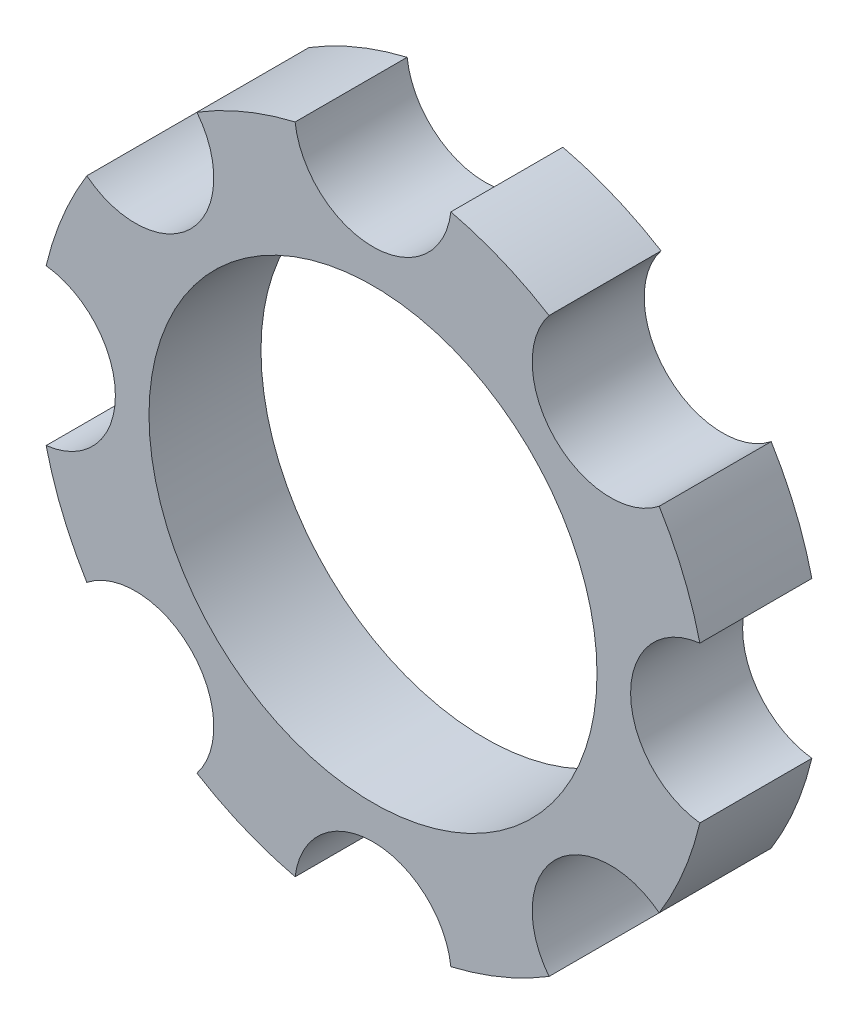
SolidWorks part; units mm, degrees
ref_plane "Front Plane" through (0, 0, 0) normal (0, 0, 1) x (1, 0, 0)
ref_plane "Top Plane" through (0, 0, 0) normal (0, 1, 0) x (1, 0, 0)
ref_plane "Right Plane" through (0, 0, 0) normal (1, 0, 0) x (0, 0, -1)
sketch "Sketch1" plane through (0, 0, 0) normal (0, 0, 1) x (1, 0, 0)
  circle A0 centre (0, 0) radius 20
  arc A1 (-6.9522, 29.1833) -> (-15.7198, 25.5517) centre (0, 0) ccw
  arc A2 (-6.9522, 29.1833) -> (6.9522, 29.1833) centre (0, 30) ccw
  arc A3 (15.7198, 25.5517) -> (25.5517, 15.7198) centre (21.2132, 21.2132) ccw
  arc A4 (29.1833, 6.9522) -> (29.1833, -6.9522) centre (30, 0) ccw
  arc A5 (25.5517, -15.7198) -> (15.7198, -25.5517) centre (21.2132, -21.2132) ccw
  arc A6 (6.9522, -29.1833) -> (-6.9522, -29.1833) centre (0, -30) ccw
  arc A7 (-15.7198, -25.5517) -> (-25.5517, -15.7198) centre (-21.2132, -21.2132) ccw
  arc A8 (-29.1833, -6.9522) -> (-29.1833, 6.9522) centre (-30, 0) ccw
  arc A9 (-25.5517, 15.7198) -> (-15.7198, 25.5517) centre (-21.2132, 21.2132) ccw
  arc A10 (-25.5517, 15.7198) -> (-29.1833, 6.9522) centre (0, 0) ccw
  arc A11 (-29.1833, -6.9522) -> (-25.5517, -15.7198) centre (0, 0) ccw
  arc A12 (-15.7198, -25.5517) -> (-6.9522, -29.1833) centre (0, 0) ccw
  arc A13 (6.9522, -29.1833) -> (15.7198, -25.5517) centre (0, 0) ccw
  arc A14 (25.5517, -15.7198) -> (29.1833, -6.9522) centre (0, 0) ccw
  arc A15 (29.1833, 6.9522) -> (25.5517, 15.7198) centre (0, 0) ccw
  arc A16 (15.7198, 25.5517) -> (6.9522, 29.1833) centre (0, 0) ccw
  point P30 (0, 0)
  dimension "D1" = 60
  dimension "D2" = 40
  dimension "D3" = 7
  dimension "D4" = 8
extrude "Boss-Extrude1" add sketch "Sketch1" along normal blind 10
